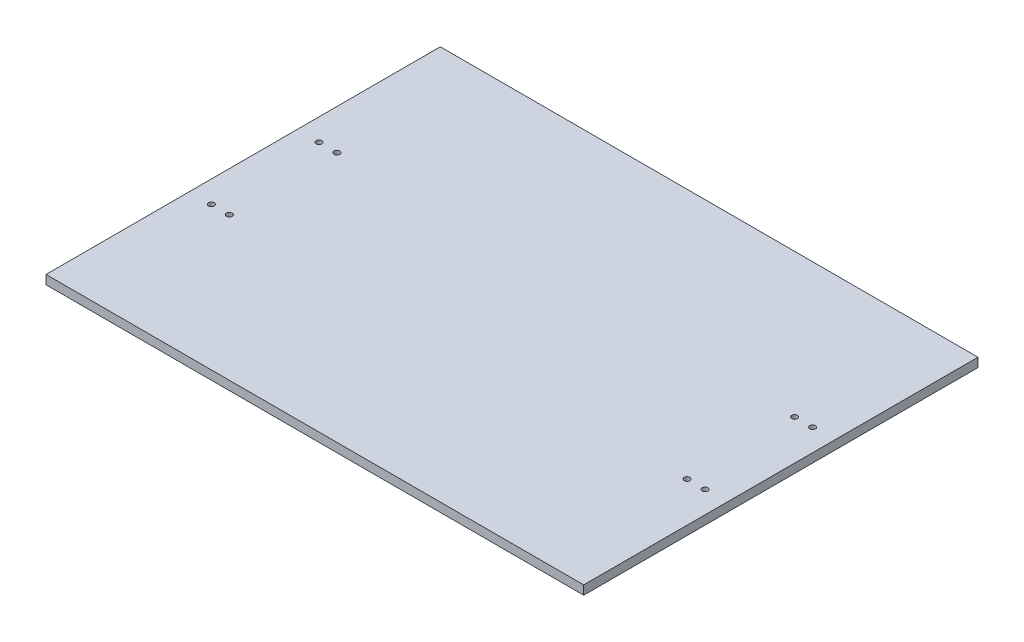
SolidWorks part; units mm, degrees
ref_plane "Front Plane" through (0, 0, 0) normal (0, 0, 1) x (1, 0, 0)
ref_plane "Top Plane" through (0, 0, 0) normal (0, 1, 0) x (1, 0, 0)
ref_plane "Right Plane" through (0, 0, 0) normal (1, 0, 0) x (0, 0, -1)
sketch "Sketch1" plane through (0, 0, 0) normal (0, 1, 0) x (1, 0, 0)
  line L0 (-150, 110) -> (150, 110)
  line L1 (-150, 110) -> (-150, -110)
  line L2 (150, 110) -> (150, -110)
  line L3 (-150, -110) -> (150, -110)
  point P3 (0, 110)
  point P8 (150, 0)
  dimension "D1" = 220
  dimension "D2" = 300
extrude "Boss-Extrude1" add sketch "Sketch1" along normal blind 5
sketch "Sketch2" plane through (0, 0, 0) normal (0, -1, 0) x (1, 0, 0)
  line L0 (150, -110) -> (-150, -110) construction
  line L1 (-150, -110) -> (-150, 110) construction
  line L2 (-150, 110) -> (150, 110) construction
  line L3 (150, 110) -> (150, -110) construction
  circle A0 centre (-137.7, -30) radius 1.6
  circle A1 centre (-127.7, -30) radius 1.6
  circle A2 centre (-137.7, 30) radius 1.6
  circle A3 centre (-127.7, 30) radius 1.6
  circle A4 centre (137.7, 30) radius 1.6
  circle A5 centre (137.7, -30) radius 1.6
  circle A6 centre (127.7, -30) radius 1.6
  circle A7 centre (127.7, 30) radius 1.6
  point P22 (0, 0)
  point P24 (130.7225, -29.7458)
  dimension "D1" = 3.2
  dimension "D2" = 3.2
  dimension "D3" = 3.2
  dimension "D4" = 3.2
  dimension "D11" = 3.2
  dimension "D12" = 3.2
  dimension "D13" = 3.2
  dimension "D14" = 3.2
  dimension "D5" = 10
  dimension "D6" = 10
  dimension "D7" = 80
  dimension "D8" = 12.3
  dimension "D9" = 80
  dimension "D10" = 12.3
  dimension "D15" = 10
  dimension "D16" = 10
  dimension "D17" = 12.3
  dimension "D18" = 80
  dimension "D19" = 12.3
  dimension "D20" = 80
extrude "Cut-Extrude1" cut sketch "Sketch2" against normal blind 10
